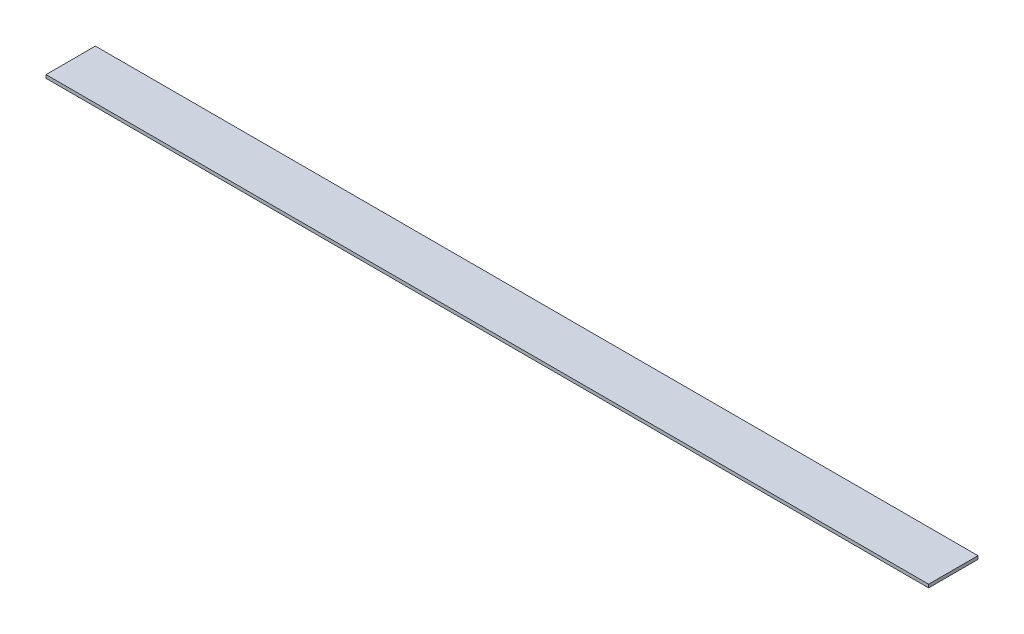
SolidWorks part; units mm, degrees
ref_plane "Front Plane" through (0, 0, 0) normal (0, 0, 1) x (1, 0, 0)
ref_plane "Top Plane" through (0, 0, 0) normal (0, 1, 0) x (1, 0, 0)
ref_plane "Right Plane" through (0, 0, 0) normal (1, 0, 0) x (0, 0, -1)
sketch "Sketch1" plane through (0, 0, 0) normal (0, 1, 0) x (1, 0, 0)
  line L1 (0, 0) -> (227, 0)
  line L2 (0, 0) -> (0, -12.7)
  line L3 (0, -12.7) -> (227, -12.7)
  line L4 (227, 0) -> (227, -12.7)
  dimension "D1" = 227
  dimension "D2" = 12.7
extrude "Boss-Extrude1" add sketch "Sketch1" against normal blind 0.8382
